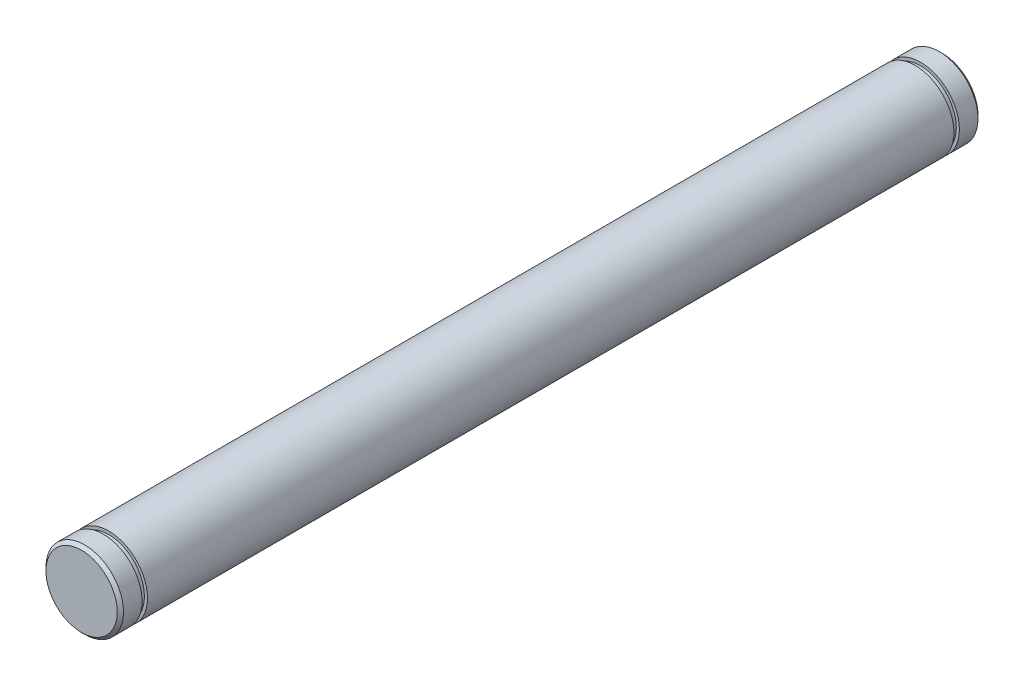
SolidWorks part; units mm, degrees
material "铸造合金钢"
ref_plane "前视基准面" through (0, 0, 0) normal (0, 0, 1) x (1, 0, 0)
ref_plane "上视基准面" through (0, 0, 0) normal (0, 1, 0) x (1, 0, 0)
ref_plane "右视基准面" through (0, 0, 0) normal (1, 0, 0) x (0, 0, -1)
sketch "草图1" plane through (0, 0, 0) normal (0, 0, 1) x (1, 0, 0)
  circle A0 centre (0, 0) radius 2.5
  dimension "D1" = 5
extrude "凸台-拉伸1" add sketch "草图1" along normal mid plane 55.5
sketch "草图2" plane through (0, 0, 0) normal (1, 0, 0) x (0, 0, -1)
  line L1 (27.75, 2.5) -> (-27.75, 2.5) construction
  line L2 (-26.35, 2.5) -> (-26, 2.5)
  line L3 (-26.35, 2.5) -> (-26.35, 2.3)
  line L4 (-26.35, 2.3) -> (-26, 2.3)
  line L5 (-26, 2.5) -> (-26, 2.3)
  line L6 (-26, 2.4) -> (26, 2.4) construction
  line L7 (26, 2.5) -> (26.35, 2.5)
  line L8 (26, 2.5) -> (26, 2.3)
  line L9 (26, 2.3) -> (26.35, 2.3)
  line L10 (26.35, 2.5) -> (26.35, 2.3)
  line L11 (26, 2.4) -> (0, 0) construction
  line L12 (0, 0) -> (0, 2.4) construction
  dimension "D1" = 52
  dimension "D2" = 0.35
  dimension "D3" = 0.2
ref_axis "基准轴1" through (0, 0, 27.75) along (0, 0, -1)
revolve "切除-旋转1" cut sketch "草图2" angle 360 about axis through (0, 0, 27.75) along (0, 0, -1)
chamfer "倒角1" distance 0.2 angle 45 2 edges at (2.5, 0, -27.75) (2.5, 0, 27.75)
